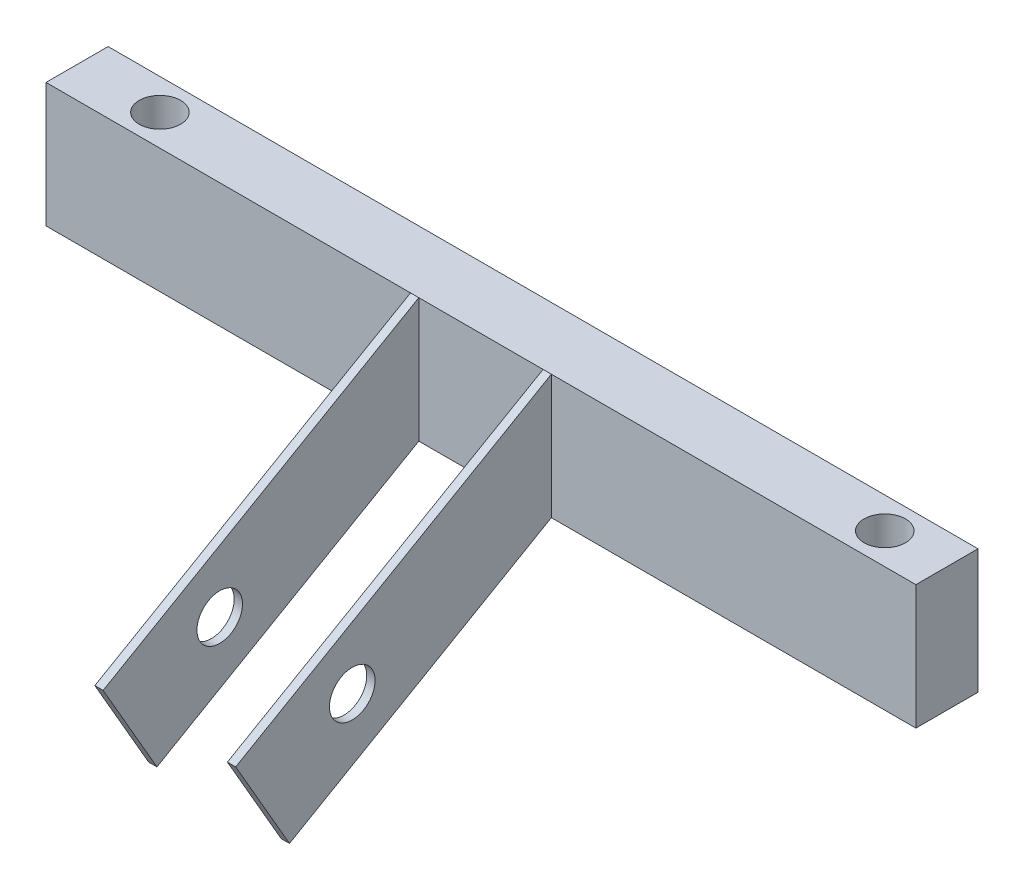
SolidWorks part; units mm, degrees
ref_plane "Plano frontal" through (0, 0, 0) normal (0, 0, 1) x (1, 0, 0)
ref_plane "Plano superior" through (0, 0, 0) normal (0, 1, 0) x (1, 0, 0)
ref_plane "Plano direito" through (0, 0, 0) normal (1, 0, 0) x (0, 0, -1)
sketch "Esboço1" plane through (0, 0, 0) normal (0, 0, 1) x (1, 0, 0)
  line L1 (0, 0) -> (60, 0)
  line L9 (60, 0) -> (60, 30)
  line L10 (60, 30) -> (-150, 30)
  line L11 (-150, 30) -> (-150, 0)
  line L12 (-150, 0) -> (0, 0)
  point P4 (0, 0)
  dimension "D2" = 30
  dimension "D1" = 60
  dimension "D3" = 210
extrude "Ressalto-extrusão1" add sketch "Esboço1" along normal blind 15
sketch "Esboço3" plane through (0, 0, 0) normal (0, -1, 0) x (-1, 0, 0)
  line L0 (150, -7.5) -> (130, -7.5)
  line L1 (150, -15) -> (150, 0) construction
  line L2 (-60, -7.5) -> (-45, -7.5)
  line L3 (-60, -15) -> (-60, 0) construction
  circle A0 centre (130, -7.5) radius 5
  circle A1 centre (-45, -7.5) radius 5
  dimension "D2" = 10
  dimension "D4" = 10
  dimension "D1" = 20
  dimension "D3" = 15
sketch "Esboço4" plane through (0, 0, 15) normal (0, 0, 1) x (1, 0, 0)
  line L0 (-66.9708, 30) -> (-66.9708, 0)
  line L1 (60, 30) -> (-150, 30) construction
  line L2 (-150, 0) -> (60, 0) construction
  line L4 (-64.9708, 0) -> (-64.9708, 30)
  line L6 (-66.9708, 30) -> (-66.9708, 43.9454)
  line L7 (-66.9708, 43.9454) -> (-64.9708, 43.9454)
  line L8 (-64.9708, 43.9454) -> (-64.9708, 30)
  line L9 (-66.9708, 0) -> (-66.9708, -20.7381)
  line L10 (-66.9708, -20.7381) -> (-64.9708, -20.7381)
  line L11 (-64.9708, -20.7381) -> (-64.9708, 0)
  dimension "D1" = 2
extrude "Ressalto-extrusão4" add sketch "Esboço4" along normal blind 41 contours L6 L7 L8 L4 L11 L10 L9 L0
sketch "Esboço6" plane through (-66.9708, 0, 0) normal (-1, 0, 0) x (0, 0, 1)
  line L0 (15, 30) -> (15, 0)
  line L1 (15, 30) -> (91.2102, -14)
  line L2 (78.2199, -36.5) -> (91.2102, -14)
  line L3 (15, 0) -> (78.2199, -36.5)
  line L4 (15, 0) -> (15, -20.7381)
  line L5 (56, -20.7381) -> (15, -20.7381) construction
  line M7 (15, -20.7381) -> (56, -20.7381)
  line M8 (56, -20.7381) -> (56, 43.9454)
  line M11 (15, 30) -> (15, 0)
  dimension "D1" = 60
  dimension "D2" = 60
  dimension "D3" = 120
extrude "Ressalto-extrusão6" add sketch "Esboço6" against normal blind 38.97 contours L3 L1 M11 M7 M8 | L3 L2 L1 M7 M8
sketch "Esboço7" plane through (-66.9708, 0, 0) normal (-1, 0, 0) x (0, 0, 1)
  line L0 (15, 30) -> (56, 6.3286)
  line L1 (56, 6.3286) -> (56, 43.9454)
  line L2 (56, 43.9454) -> (15, 43.9454)
  line L3 (15, 43.9454) -> (15, 30)
  line L4 (15, 0) -> (50.9194, -20.7381)
  line L5 (50.9194, -20.7381) -> (15, -20.7381)
  line L6 (15, -20.7381) -> (15, 0)
extrude "Corte-extrusão4" cut sketch "Esboço7" against normal blind 38.97
sketch "Esboço8" plane through (-66.9708, 0, 0) normal (-1, 0, 0) x (0, 0, 1)
  line L0 (15, 30) -> (91.2102, -14)
  line L1 (91.2102, -14) -> (78.2199, -36.5)
  line L2 (78.2199, -36.5) -> (15, 0)
  line L3 (15, 0) -> (15, 30)
extrude "Corte-extrusão5" cut sketch "Esboço8" against normal blind 4.97
shell "Casca1" thickness 2
sketch "Esboço9" plane through (0, 28.9952, 16.7404) normal (0, 0.866, 0.5) x (1, 0, 0)
  line L0 (-28.0008, 2.0096) -> (-30.0008, 2.0096)
  line L1 (-28.0008, 2.0096) -> (-62.0008, 2.0096) construction
  line L2 (-62.0008, -85.9904) -> (-60.0008, -85.9904)
  line L3 (-28.0008, -85.9904) -> (-62.0008, -85.9904) construction
  line L5 (-30.0008, 2.0096) -> (-60.0008, 2.0096)
  line L6 (-30.0008, 2.0096) -> (-30.0008, -85.9904)
  line L7 (-30.0008, -85.9904) -> (-60.0008, -85.9904)
  line L8 (-60.0008, 2.0096) -> (-60.0008, -85.9904)
  line M3 (-28.0008, 2.0096) -> (-62.0008, 2.0096)
  line M5 (-62.0008, -85.9904) -> (-28.0008, -85.9904)
  dimension "D1" = 2
  dimension "D2" = 2
extrude "Corte-extrusão6" cut sketch "Esboço9" against normal blind 2 contours L8 L6 M3 M5
sketch "Esboço11" plane through (0, 6.4952, 3.75) normal (0, -0.866, -0.5) x (-1, 0, 0)
  line L0 (28.0008, -85.9904) -> (30.0008, -85.9904)
  line L1 (28.0008, -85.9904) -> (62.0008, -85.9904) construction
  line L2 (30.0008, -85.9904) -> (30.0008, -12.9904)
  line L3 (62.0008, -12.9904) -> (28.0008, -12.9904) construction
  line L4 (30.0008, -12.9904) -> (60.0008, -12.9904)
  line L5 (60.0008, -12.9904) -> (60.0008, -85.9904)
  line L6 (60.0008, -85.9904) -> (30.0008, -85.9904)
  line M2 (62.0008, -12.9904) -> (28.0008, -12.9904)
  line M4 (28.0008, -85.9904) -> (62.0008, -85.9904)
  dimension "D1" = 2
  dimension "D2" = 30
extrude "Corte-extrusão7" cut sketch "Esboço11" against normal blind 2 contours L5 L2 M2 M4
sketch "Esboço12" plane through (0, 30, 0) normal (0, 1, 0) x (1, 0, 0)
  line L0 (-60.0008, -15) -> (-60.0008, -91.2102) construction
  line L1 (-30.0008, -15) -> (-60.0008, -15)
  line L2 (-30.0008, -15) -> (-30.0008, -21.0769)
  line L3 (-30.0008, -21.0769) -> (-60.0008, -21.0769)
  line L4 (-60.0008, -15) -> (-60.0008, -21.0769)
extrude "Corte-extrusão8" cut sketch "Esboço12" against normal blind 73
sketch "Esboço13" plane through (-62.0008, 0, 0) normal (-1, 0, 0) x (0, 0, 1)
  line L0 (91.2102, -14) -> (84.715, -25.25)
  line L1 (78.2199, -36.5) -> (91.2102, -14) construction
  line L2 (84.715, -25.25) -> (63.0644, -12.75)
  circle A0 centre (63.0644, -12.75) radius 5.5
  dimension "D2" = 11
  dimension "D1" = 25
extrude "Corte-extrusão9" cut sketch "Esboço13" against normal blind 73
sketch "Esboço14" plane through (-150, 0, 0) normal (-1, 0, 0) x (0, 0, 1)
  line L0 (15, 30) -> (15, 0) construction
  line L1 (0, 30) -> (15, 30)
  line L2 (0, 30) -> (0, 0)
  line L3 (0, 0) -> (15, 0)
  line L4 (15, 30) -> (15, 0)
  line L5 (15, 0) -> (78.2199, -36.5) construction
extrude "Ressalto-extrusão8" add sketch "Esboço14" against normal blind 210
extrude "Corte-extrusão10" cut sketch "Esboço3" against normal blind 210 contours A1 | A0
